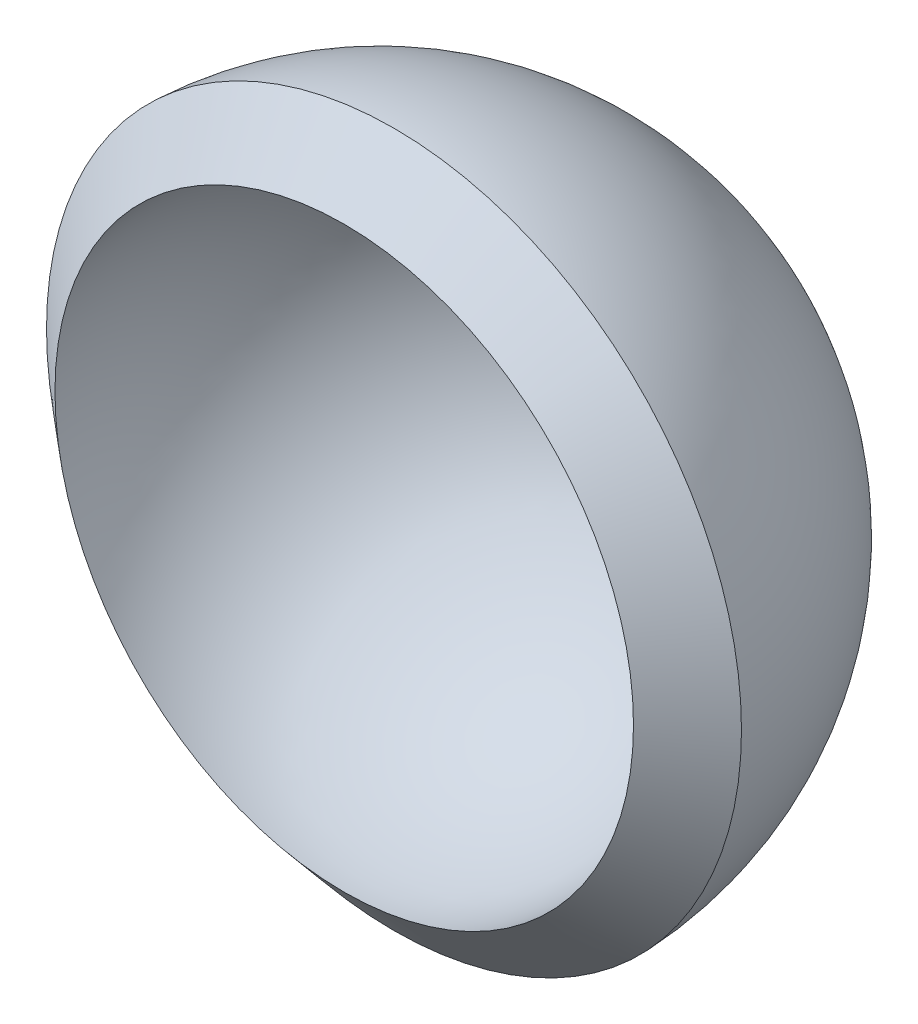
SolidWorks part; units mm, degrees
ref_plane "Спереди" through (0, 0, 0) normal (0, 0, 1) x (1, 0, 0)
ref_plane "Сверху" through (0, 0, 0) normal (0, 1, 0) x (1, 0, 0)
ref_plane "Справа" through (0, 0, 0) normal (1, 0, 0) x (0, 0, -1)
sketch "Sketch1" plane through (0, 0, 0) normal (0, 1, 0) x (1, 0, 0)
  line L0 (2.9777, 11.965) -> (3.577, 12.4774)
  line L1 (0, 16.26) -> (0, 10.6192) construction
  line L2 (0, 15.33) -> (0, 15.91)
  arc A2 (2.9777, 11.965) -> (0, 15.33) centre (0, 12.33) ccw
  arc A3 (3.577, 12.4774) -> (0, 15.91) centre (0, 12.33) ccw
revolve "Revolve1" add sketch "Sketch1" angle 360 about L1
